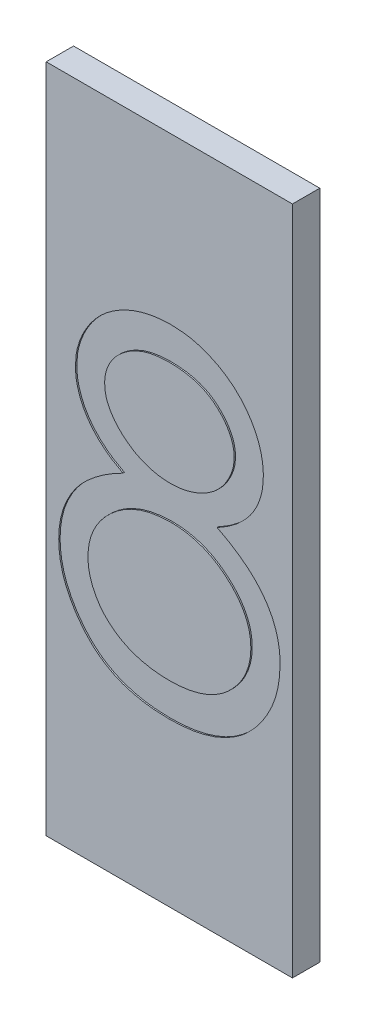
SolidWorks part; units mm, degrees
ref_plane "正面" through (0, 0, 0) normal (0, 0, 1) x (1, 0, 0)
ref_plane "平面" through (0, 0, 0) normal (0, 1, 0) x (1, 0, 0)
ref_plane "右側面" through (0, 0, 0) normal (1, 0, 0) x (0, 0, -1)
sketch "ｽｹｯﾁ1" plane through (0, 0, 0) normal (0, 0, 1) x (1, 0, 0)
  line L0 (18, 0) -> (0, 0)
  line L1 (18, 49) -> (0, 49)
  line L2 (0, 0) -> (0, 49)
  line L4 (18, 0) -> (18, 49)
extrude "ﾎﾞｽ - 押し出し1" add sketch "ｽｹｯﾁ1" along normal blind 2
sketch "ｽｹｯﾁ2" plane through (0, 0, 2) normal (0, 0, 1) x (1, 0, 0)
  text T0 "8" font "Century Gothic" height in points 90
extrude "ｶｯﾄ - 押し出し1" cut sketch "ｽｹｯﾁ2" against normal blind 0.1
